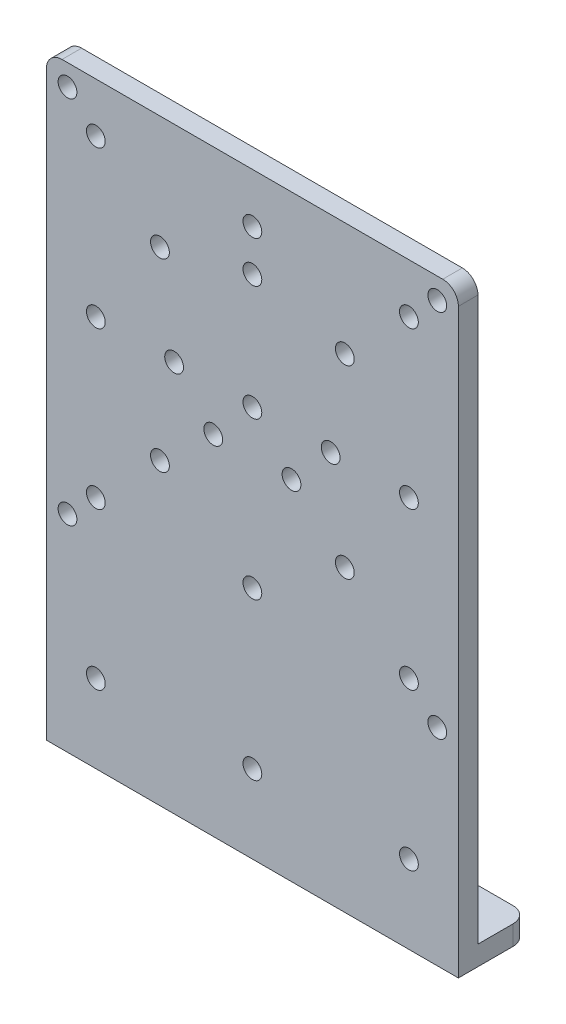
SolidWorks part; units mm, degrees
ref_plane "Front Plane" through (0, 0, 0) normal (0, 0, 1) x (1, 0, 0)
ref_plane "Top Plane" through (0, 0, 0) normal (0, 1, 0) x (1, 0, 0)
ref_plane "Right Plane" through (0, 0, 0) normal (1, 0, 0) x (0, 0, -1)
sketch "Sketch1" plane through (0, 0, 0) normal (0, 1, 0) x (1, 0, 0)
  line L1 (0, 0) -> (66.8528, 0)
  line L2 (0, 0) -> (0, 11.43)
  line L3 (0, 11.43) -> (66.8528, 11.43)
  line L4 (66.8528, 0) -> (66.8528, 11.43)
  dimension "D1" = 66.8528
  dimension "D2" = 11.43
extrude "Boss-Extrude1" add sketch "Sketch1" along normal blind 3.175
sketch "Sketch2" plane through (0, 3.175, 0) normal (0, 1, 0) x (1, 0, 0)
  line L0 (66.8528, 0) -> (66.8528, 11.43) construction
  line L1 (0, 11.43) -> (66.8528, 11.43)
  line L2 (0, 11.43) -> (0, 7.366)
  line L4 (66.8528, 11.43) -> (66.8528, 7.366)
  line L5 (0, 0) -> (33.4264, 0)
  line L6 (0, 0) -> (66.8528, 0) construction
  line L7 (33.4264, 0) -> (33.4264, 3.175)
  line L8 (33.4264, 3.175) -> (66.8528, 3.175)
  line L10 (66.8528, 3.175) -> (0, 3.175)
  line L11 (66.8528, 3.175) -> (66.8528, 0)
  line L12 (66.8528, 0) -> (0, 0)
  line L13 (0, 3.175) -> (0, 0)
  dimension "D1" = 33.4264
  dimension "D2" = 3.175
  dimension "D3" = 33.4264
  dimension "D4" = 3.175
  dimension "D5" = 66.8528
extrude "Boss-Extrude2" add sketch "Sketch2" along normal blind 93.7514 contours L11 L12 L13 L10
sketch "Sketch3" plane through (0, 0, 0) normal (0, 0, 1) x (1, 0, 0)
  line L0 (0, 0) -> (33.4264, 0)
  line L1 (0, 0) -> (66.8528, 0) construction
  line L2 (33.4264, 0) -> (33.4264, 63.5)
  line L4 (8.0264, 88.9) -> (58.8264, 88.9)
  line L5 (8.0264, 88.9) -> (8.0264, 38.1)
  line L6 (8.0264, 38.1) -> (58.8264, 38.1)
  line L7 (58.8264, 88.9) -> (58.8264, 38.1)
  line L8 (8.0264, 88.9) -> (58.8264, 38.1) construction
  line L9 (8.0264, 38.1) -> (58.8264, 88.9) construction
  line L14 (20.7264, 76.2) -> (46.1264, 50.8) construction
  line L15 (20.7264, 50.8) -> (46.1264, 76.2) construction
  line L16 (48.4264, 48.5) -> (18.4264, 48.5)
  line L17 (48.4264, 48.5) -> (48.4264, 78.5)
  line L18 (48.4264, 78.5) -> (18.4264, 78.5)
  line L19 (18.4264, 48.5) -> (18.4264, 78.5)
  line L20 (48.4264, 48.5) -> (18.4264, 78.5) construction
  line L21 (48.4264, 78.5) -> (18.4264, 48.5) construction
  line L22 (63.4264, 33.5) -> (3.4264, 33.5)
  line L23 (63.4264, 33.5) -> (63.4264, 93.5)
  line L24 (63.4264, 93.5) -> (3.4264, 93.5)
  line L25 (3.4264, 33.5) -> (3.4264, 93.5)
  line L26 (63.4264, 33.5) -> (3.4264, 93.5) construction
  line L27 (63.4264, 93.5) -> (3.4264, 33.5) construction
  dimension "D1" = 33.4264
  dimension "D2" = 63.5
  dimension "D3" = 50.8
  dimension "D4" = 50.8
  dimension "D5" = 25.4
  dimension "D6" = 25.4
  dimension "D7" = 30
  dimension "D8" = 30
  dimension "D9" = 60
hole_wizard "Tapped Hole for #4-40 Helicoil1" positions "Sketch4" profile "Sketch5" tap size "#4-40" standard "Helicoil® Inch" end condition through all
sketch "Sketch4" plane through (0, 0, 0) normal (0, 0, 1) x (1, 0, 0)
  point P0 (8.0264, 88.9)
sketch "Sketch5" plane through (8.0264, 88.9, 0) normal (1, 0, 0) x (0, -1, 0)
  line L0 (0, 0) -> (0, 11.43)
  line L1 (0, 11.43) -> (1.524, 11.43)
  line L2 (1.524, 11.43) -> (1.524, 0)
  line L5 (1.524, 0) -> (0, 0)
  line L11 (0, -6.35) -> (0, 107.95) construction
  dimension "Thru Tap Drill Dia." = 3.048
  dimension "Thru Tap Drill Depth" = 11.43
cosmetic thread "Hole Thread1" parameters "D1"=3.556, "D2"=3.7414
pattern_linear "LPattern1" count 3 spacing 25.4 along (1, 0, 0) count 4 spacing 25.4 along (0, -1, 0) of "Tapped Hole for #4-40 Helicoil1"
cosmetic thread "Hole Thread2" parameters "D1"=3.556, "D2"=3.7414
cosmetic thread "Hole Thread3" parameters "D1"=3.556, "D2"=3.7414
cosmetic thread "Hole Thread4" parameters "D1"=3.556, "D2"=3.7414
cosmetic thread "Hole Thread5" parameters "D1"=3.556, "D2"=3.7414
cosmetic thread "Hole Thread6" parameters "D1"=3.556, "D2"=3.7414
cosmetic thread "Hole Thread7" parameters "D1"=3.556, "D2"=3.7414
cosmetic thread "Hole Thread8" parameters "D1"=3.556, "D2"=3.7414
cosmetic thread "Hole Thread9" parameters "D1"=3.556, "D2"=3.7414
cosmetic thread "Hole Thread10" parameters "D1"=3.556, "D2"=3.7414
cosmetic thread "Hole Thread11" parameters "D1"=3.556, "D2"=3.7414
cosmetic thread "Hole Thread12" parameters "D1"=3.556, "D2"=3.7414
sketch "Sketch6" plane through (0, 3.175, 0) normal (0, 1, 0) x (1, 0, 0)
  line L0 (0, 11.43) -> (0, 8.001)
  line L1 (0, 11.43) -> (0, 3.175) construction
  line L2 (0, 8.001) -> (8.0264, 8.001)
  line L3 (8.0264, 8.001) -> (33.4264, 8.001)
  line L4 (33.4264, 8.001) -> (58.8264, 8.001)
  dimension "D1" = 3.429
  dimension "D2" = 8.0264
  dimension "D3" = 25.4
  dimension "D4" = 25.4
hole_wizard "#30 (0.1285) Diameter Hole1" positions "Sketch9" profile "Sketch8" hole size "#30" standard "ANSI Inch" end condition through all
sketch "Sketch9" plane through (0, 3.175, 0) normal (0, 1, 0) x (1, 0, 0)
  point P0 (8.0264, 8.001)
  point P3 (33.4264, 8.001)
  point P6 (58.8264, 8.001)
sketch "Sketch8" plane through (8.0264, 3.175, -8.001) normal (1, 0, 0) x (0, 0, 1)
  line L0 (0, 0) -> (0, 3.175)
  line L1 (0, 3.175) -> (1.6319, 3.175)
  line L2 (1.6319, 3.175) -> (1.632, 0)
  line L5 (1.632, 0) -> (0, 0)
  line L11 (0, -6.35) -> (0, 107.95) construction
  dimension "Thru Hole Dia." = 3.2639
  dimension "Thru Hole Depth" = 3.175
ref_plane "Plane1" through (20.7264, 0, 0) normal (-1, 0, 0) x (0, 0, 1)
ref_plane "Plane2" through (46.1264, 0, 0) normal (-1, 0, 0) x (0, 0, 1)
sketch "Sketch15" plane through (46.1264, 0, 0) normal (-1, 0, 0) x (0, 0, 1)
  line L0 (-11.43, 3.175) -> (-3.175, 28.8026)
  line L1 (-3.175, 96.9264) -> (-3.175, 3.175) construction
rib "Rib3" sketch "Sketch15" sketch "Sketch15" thickness 2.54 extrusion direction parallel to sketch draft on no parameters "D1"=2.54
sketch "Sketch16" plane through (20.7264, 0, 0) normal (-1, 0, 0) x (0, 0, 1)
  line L0 (-11.43, 3.175) -> (-3.175, 28.8026)
  line L1 (-11.43, 3.175) -> (-8.001, 3.175) construction
  line L2 (-11.43, 3.175) -> (-3.175, 28.8026) construction
rib "Rib4" sketch "Sketch16" sketch "Sketch16" thickness 2.54 extrusion direction parallel to sketch draft on no parameters "D1"=2.54
sketch "Sketch17" plane through (0, 0, 0) normal (0, 0, 1) x (1, 0, 0)
  line L0 (33.4264, 63.5) -> (33.4264, 56.515)
  line L1 (8.0264, 88.9) -> (58.8264, 38.1) construction
  line L2 (33.4264, 0) -> (33.4264, 63.5) construction
  line L3 (33.4264, 56.515) -> (39.7764, 56.515)
  line L4 (33.4264, 56.515) -> (27.0764, 56.515)
  line L5 (33.4264, 63.5) -> (33.4264, 82.169)
  line L6 (33.4264, 63.5) -> (20.7264, 63.5)
  line L7 (33.4264, 63.5) -> (46.1264, 63.5)
  dimension "D1" = 18.669
  dimension "D2" = 6.985
  dimension "D3" = 6.35
  dimension "D4" = 6.35
  dimension "D5" = 12.7
  dimension "D6" = 12.7
hole_wizard "Tapped Hole for #4-40 Helicoil3" positions "Sketch18" profile "Sketch19" tap size "#4-40" standard "Helicoil® Inch" end condition through all
sketch "Sketch18" plane through (0, 0, 0) normal (0, 0, 1) x (1, 0, 0)
  point P0 (27.0764, 56.515)
  point P3 (39.7764, 56.515)
  point P6 (33.4264, 82.169)
  point P10 (20.7264, 63.5)
  point P13 (46.1264, 63.5)
sketch "Sketch19" plane through (27.0764, 56.515, 0) normal (1, 0, 0) x (0, -1, 0)
  line L0 (0, 0) -> (0, 11.43)
  line L1 (0, 11.43) -> (1.524, 11.43)
  line L2 (1.524, 11.43) -> (1.524, 0)
  line L5 (1.524, 0) -> (0, 0)
  line L11 (0, -6.35) -> (0, 107.95) construction
  dimension "Thru Tap Drill Dia." = 3.048
  dimension "Thru Tap Drill Depth" = 11.43
cosmetic thread "Hole Thread21" parameters "D1"=3.175, "D2"=3.7414
cosmetic thread "Hole Thread22" parameters "D1"=3.175, "D2"=3.7414
cosmetic thread "Hole Thread23" parameters "D1"=3.175, "D2"=3.7414
cosmetic thread "Hole Thread32" parameters "D1"=3.175, "D2"=3.7414
cosmetic thread "Hole Thread33" parameters "D1"=3.175, "D2"=3.7414
fillet "Fillet1" radius 2.54 8 edges at (0, 1.5875, -11.43) (66.8528, 1.5875, -11.43) (47.3964, 15.9888, -3.175) (21.9964, 15.9888, -3.175) (19.4564, 15.9888, -3.175) (44.8564, 15.9888, -3.175) (0, 96.9264, -1.5875) (66.8528, 96.9264, -1.5875)
hole_wizard "Tapped Hole for #4-40 Helicoil4" positions "Sketch20" profile "Sketch21" tap size "#4-40" standard "Helicoil® Inch" end condition through all
sketch "Sketch20" plane through (0, 0, 0) normal (0, 0, 1) x (1, 0, 0)
  point P0 (3.4264, 93.5)
  point P3 (3.4264, 33.5)
  point P6 (63.4264, 33.5)
  point P9 (63.4264, 93.5)
  point P12 (18.4264, 78.5)
  point P15 (48.4264, 78.5)
  point P18 (48.4264, 48.5)
  point P21 (18.4264, 48.5)
sketch "Sketch21" plane through (3.4264, 93.5, 0) normal (1, 0, 0) x (0, -1, 0)
  line L0 (0, 0) -> (0, 11.43)
  line L1 (0, 11.43) -> (1.524, 11.43)
  line L2 (1.524, 11.43) -> (1.524, 0)
  line L5 (1.524, 0) -> (0, 0)
  line L11 (0, -6.35) -> (0, 107.95) construction
  dimension "Thru Tap Drill Dia." = 3.048
  dimension "Thru Tap Drill Depth" = 11.43
cosmetic thread "Hole Thread24" parameters "D1"=3.556, "D2"=3.7414
cosmetic thread "Hole Thread25" parameters "D1"=3.556, "D2"=3.7414
cosmetic thread "Hole Thread26" parameters "D1"=3.556, "D2"=3.7414
cosmetic thread "Hole Thread27" parameters "D1"=3.556, "D2"=3.7414
cosmetic thread "Hole Thread28" parameters "D1"=3.556, "D2"=3.7414
cosmetic thread "Hole Thread29" parameters "D1"=3.556, "D2"=3.7414
cosmetic thread "Hole Thread30" parameters "D1"=3.556, "D2"=3.7414
cosmetic thread "Hole Thread31" parameters "D1"=3.556, "D2"=3.7414
